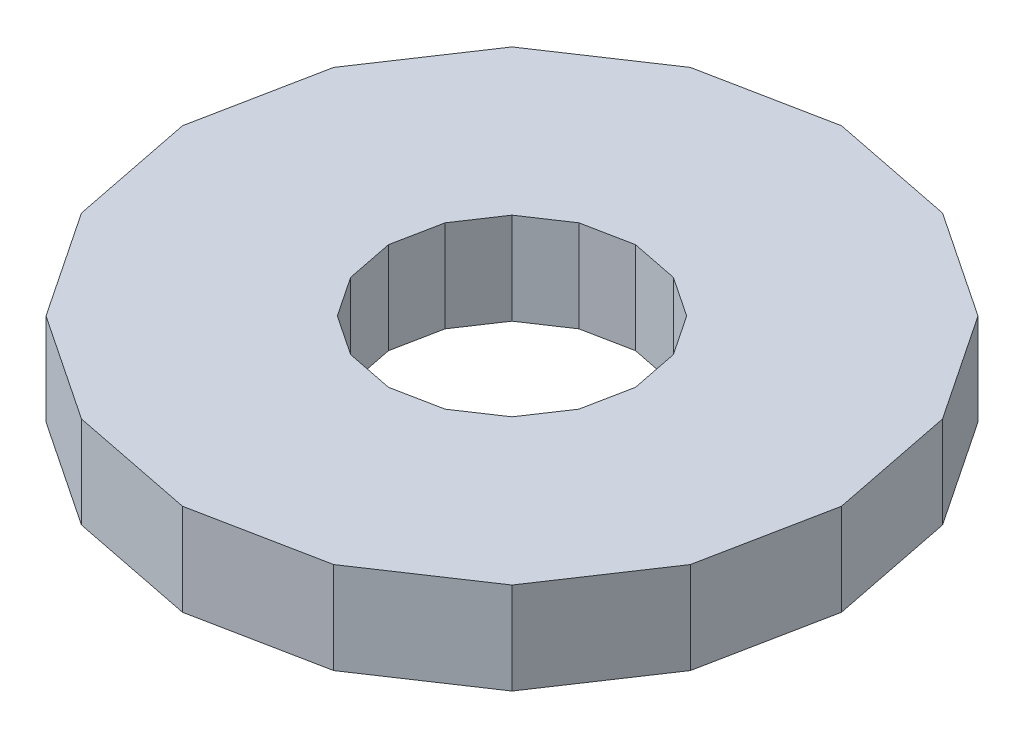
SolidWorks part; units mm, degrees
ref_plane "Front Plane" through (0, 0, 0) normal (0, 0, 1) x (1, 0, 0)
ref_plane "Top Plane" through (0, 0, 0) normal (0, 1, 0) x (1, 0, 0)
ref_plane "Right Plane" through (0, 0, 0) normal (1, 0, 0) x (0, 0, -1)
sketch "Sketch2" plane through (0, 0, 0) normal (0, 1, 0) x (1, 0, 0)
  line L0 (-68.353, 0) -> (-25.6219, 0) construction
  line L1 (-68.353, 0) -> (-63.1499, -26.1575)
  line L2 (-63.1499, -26.1575) -> (-48.3328, -48.3328)
  line L3 (-48.3328, -48.3328) -> (-26.1575, -63.1499)
  line L4 (-26.1575, -63.1499) -> (0, -68.353)
  line L5 (0, -68.353) -> (26.1575, -63.1499)
  line L6 (26.1575, -63.1499) -> (48.3328, -48.3328)
  line L7 (48.3328, -48.3328) -> (63.1499, -26.1575)
  line L8 (63.1499, -26.1575) -> (68.353, 0)
  line L9 (68.353, 0) -> (63.1499, 26.1575)
  line L10 (63.1499, 26.1575) -> (48.3328, 48.3328)
  line L11 (48.3328, 48.3328) -> (26.1575, 63.1499)
  line L12 (26.1575, 63.1499) -> (0, 68.353)
  line L13 (0, 68.353) -> (-26.1575, 63.1499)
  line L14 (-26.1575, 63.1499) -> (-48.3328, 48.3328)
  line L15 (-48.3328, 48.3328) -> (-63.1499, 26.1575)
  line L16 (-63.1499, 26.1575) -> (-68.353, 0)
  line L17 (-25.6219, 0) -> (-23.6715, -9.8051)
  line L18 (-23.6715, -9.8051) -> (-18.1174, -18.1174)
  line L19 (-18.1174, -18.1174) -> (-9.8051, -23.6715)
  line L20 (-9.8051, -23.6715) -> (0, -25.6219)
  line L21 (0, -25.6219) -> (9.8051, -23.6715)
  line L22 (9.8051, -23.6715) -> (18.1174, -18.1174)
  line L23 (18.1174, -18.1174) -> (23.6715, -9.8051)
  line L24 (23.6715, -9.8051) -> (25.6219, 0)
  line L25 (25.6219, 0) -> (23.6715, 9.8051)
  line L26 (23.6715, 9.8051) -> (18.1174, 18.1174)
  line L27 (18.1174, 18.1174) -> (9.8051, 23.6715)
  line L28 (9.8051, 23.6715) -> (0, 25.6219)
  line L29 (0, 25.6219) -> (-9.8051, 23.6715)
  line L30 (-9.8051, 23.6715) -> (-18.1174, 18.1174)
  line L31 (-18.1174, 18.1174) -> (-23.6715, 9.8051)
  line L32 (-23.6715, 9.8051) -> (-25.6219, 0)
  line L33 (0, 0) -> (-25.6219, 0) construction
  circle A0 centre (0, 0) radius 67.0396 construction
  circle A1 centre (0, 0) radius 25.1296 construction
  dimension "D1" = 26.67
  dimension "D2" = 41.91
extrude "Boss-Extrude2" add sketch "Sketch2" along normal blind 19.05
